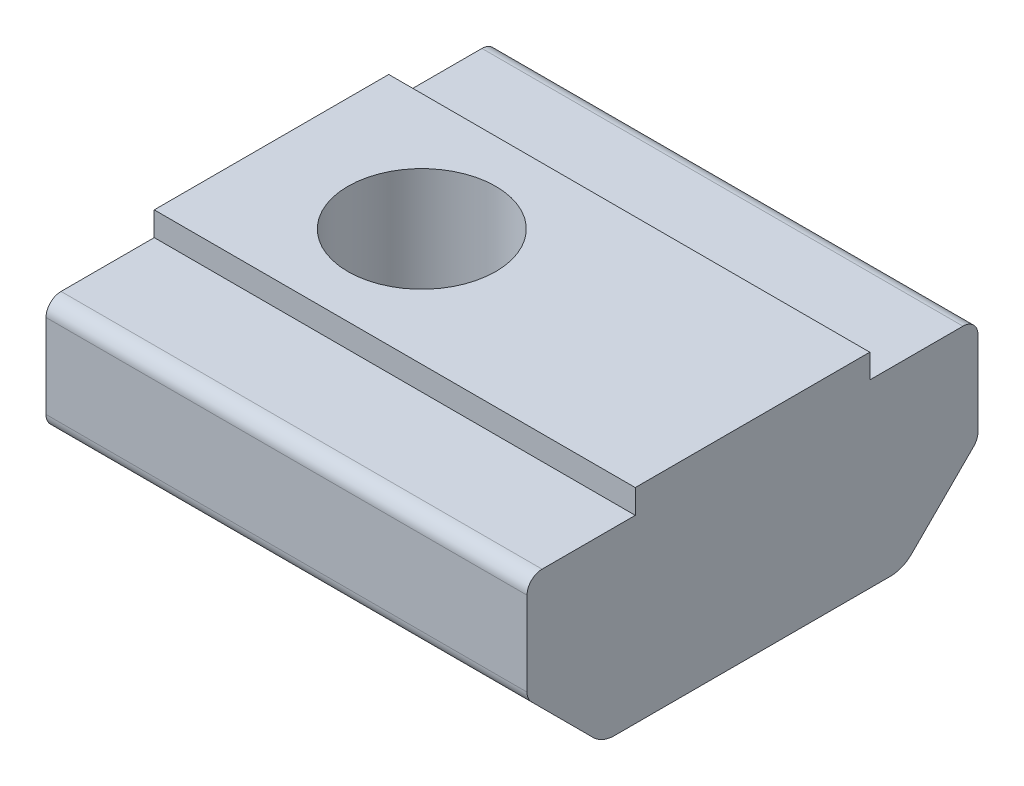
SolidWorks part; units mm, degrees
ref_plane "Front Plane" through (0, 0, 0) normal (0, 0, 1) x (1, 0, 0)
ref_plane "Top Plane" through (0, 0, 0) normal (0, 1, 0) x (1, 0, 0)
ref_plane "Right Plane" through (0, 0, 0) normal (1, 0, 0) x (0, 0, -1)
ref_plane "Plane1" through (-5, 0, 0) normal (1, 0, 0) x (0, 0, -1)
ref_plane "Plane2" through (7, 0, 0) normal (1, 0, 0) x (0, 0, -1)
sketch "Sketch1" plane through (-5, 0, 0) normal (1, 0, 0) x (0, 0, -1)
  line L0 (3.9, 0) -> (-3.9, 0)
  line L1 (-3.9, 0) -> (-3.9, -0.8)
  line L2 (-3.9, -0.8) -> (-7.5, -0.8)
  line L3 (-7.5, -0.8) -> (-7.5, -4.3)
  line L4 (-7.5, -4.3) -> (-5, -6.8)
  line L5 (-5, -6.8) -> (5, -6.8)
  line L6 (5, -6.8) -> (7.5, -4.3)
  line L7 (7.5, -4.3) -> (7.5, -0.8)
  line L8 (7.5, -0.8) -> (3.9, -0.8)
  line L9 (3.9, -0.8) -> (3.9, 0)
  line L10 (0, 0) -> (0, -6.8) construction
  point P15 (-7.5, -4.3)
  point P18 (-5, -6.8)
  point P24 (7.5, -4.3)
  dimension "FIX_8" = 10
  dimension "FIX_3" = 15
  dimension "FIX_6" = 7.8
  dimension "FIX_4" = 6.8
  dimension "FIX_5" = 6
  dimension "FIX_7" = 3.5
extrude "Boss-Extrude1" add sketch "Sketch1" along normal blind 16
fillet "Fillet1" radius 1 2 edges at (3, -6.8, 5) (3, -6.8, -5)
fillet "Fillet2" radius 0.5 4 edges at (3, -4.3, -7.5) (3, -0.8, -7.5) (3, -0.8, 7.5) (3, -4.3, 7.5)
sketch "Sketch2" plane through (7, 0, 0) normal (1, 0, 0) x (0, 0, -1)
  line L0 (0, 1.6655) -> (0, -9.505) construction
  line L2 (0, -6.6) -> (2.35, -6.6)
  line L3 (0, -6.6) -> (0, -6.8)
  line L4 (0, -6.8) -> (2.35, -6.8)
  line L5 (2.35, -6.6) -> (2.35, -6.8)
  dimension "FIX_14" = 0.2
  dimension "FIX_13" = 2.35
  dimension "FIX_12" = 6.8
revolve "Cut-Revolve1" cut sketch "Sketch2" angle 360 about L0
sketch "Sketch3" plane through (7, 0, 0) normal (1, 0, 0) x (0, 0, -1)
  line L0 (0, 0) -> (0, -7.8) construction
  line L1 (1.99, -6.6) -> (0, -6.6) construction
  line L2 (1.99, -7.8) -> (0, -7.8) construction
  line L3 (1.99, -6.6) -> (0, -6.6)
  line L4 (0, -6.6) -> (0, -7.8)
  arc A0 (0, -7.8) -> (1.99, -6.6) centre (0, -5.55) ccw
  dimension "FIX_18" = 4.5
  dimension "FIX_16" = 7.8
  dimension "FIX_17" = 6.6
revolve "Revolve1" add sketch "Sketch3" angle 360 about L0
hole_wizard "Tapped Hole1" positions "Sketch5" profile "Sketch4" tap size "M6x1.0" standard "JIS" end condition through all
sketch "Sketch5" plane through (0, 0, 0) normal (0, 1, 0) x (1, 0, 0)
  point P0 (0, 0)
cosmetic thread "Thread1" parameters "NFIX_1"=6
sketch "Sketch4" plane through (0, 0, 0) normal (1, 0, 0) x (0, 0, 1)
  line L0 (0, 0) -> (0, 7.8)
  line L1 (0, 7.8) -> (2.4585, 7.8)
  line L2 (2.4585, 7.8) -> (2.4585, 0)
  line L5 (2.4585, 0) -> (0, 0)
  line L11 (0, 0) -> (0, 7.8) construction
  dimension "Thru Tap Drill Dia." = 4.917
  dimension "Thru Tap Drill Depth" = 7.8
